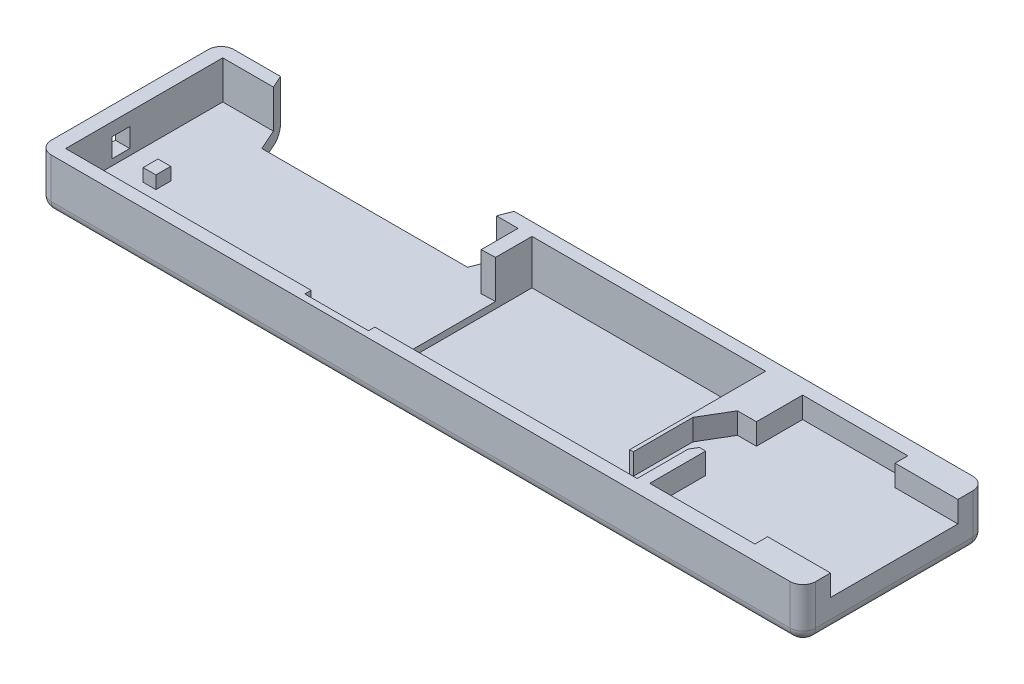
SolidWorks part; units mm, degrees
ref_plane "前视基准面" through (0, 0, 0) normal (0, 0, 1) x (1, 0, 0)
ref_plane "上视基准面" through (0, 0, 0) normal (0, 1, 0) x (1, 0, 0)
ref_plane "右视基准面" through (0, 0, 0) normal (1, 0, 0) x (0, 0, -1)
sketch "草图3" plane through (0, 0, 0) normal (0, 1, 0) x (1, 0, 0)
  line L1 (-39.9314, 29.2531) -> (140.0686, 29.2531)
  line L2 (-39.9314, 29.2531) -> (-39.9314, -13.7469)
  line L3 (-39.9314, -13.7469) -> (140.0686, -13.7469)
  line L4 (140.0686, 29.2531) -> (140.0686, -13.7469)
extrude "凸台-拉伸1" add sketch "草图3" along normal blind 12
sketch "草图4" plane through (0, 0, 0) normal (0, 1, 0) x (1, 0, 0)
  line L0 (-22.4696, -5.8589) -> (26.0023, -5.8589)
  line L1 (-39.9314, -13.7469) -> (140.0686, -13.7469) construction
  line L2 (-25.9314, -13.7469) -> (29.0686, -13.7469)
  line L5 (-25.9314, -13.7469) -> (-22.4696, -5.8589)
  line L6 (29.0686, -13.7469) -> (26.0023, -5.8589)
  point P11 (-22.4696, -5.8589)
  point P12 (26.0023, -5.8589)
extrude "切除-拉伸1" cut sketch "草图4" along normal blind 52
sketch "草图5" plane through (0, 12, 0) normal (0, 1, 0) x (1, 0, 0)
  line L6 (140.0686, -13.7469) -> (140.0686, 29.2531) construction
  line L7 (140.0686, 7.7531) -> (140.0686, 22.7531)
  line L8 (140.0686, 7.7531) -> (140.0686, -7.2469)
  line L9 (140.0686, 22.7531) -> (125.2765, 22.7531)
  line L10 (125.2765, 22.7531) -> (125.2765, -7.2469)
  line L11 (125.2765, -7.2469) -> (140.0686, -7.2469)
  point P0 (140.0686, 7.7531)
extrude "切除-拉伸2" cut sketch "草图5" against normal blind 5
sketch "草图7" plane through (0, 12, 0) normal (0, 1, 0) x (1, 0, 0)
  line L0 (125.2765, 22.7531) -> (125.2765, -7.2469) construction
  line L1 (125.2765, 7.7531) -> (125.2765, 25.7531)
  line L2 (125.2765, 7.7531) -> (125.2765, -10.2469)
  line L3 (125.2765, -10.2469) -> (100.5008, -10.2469)
  line L4 (100.5008, -10.2469) -> (100.5008, 25.7531)
  line L5 (100.5008, 25.7531) -> (125.2765, 25.7531)
  point P0 (125.2765, 7.7531)
extrude "切除-拉伸3" cut sketch "草图7" against normal blind 5
sketch "草图8" plane through (0, 12, 0) normal (0, 1, 0) x (1, 0, 0)
  line L1 (36.2763, 26.2531) -> (91.2763, 26.2531)
  line L2 (36.2763, 26.2531) -> (36.2763, -10.7469)
  line L3 (36.2763, -10.7469) -> (91.2763, -10.7469)
  line L4 (91.2763, 26.2531) -> (91.2763, -10.7469)
  line L6 (140.0686, 29.2531) -> (-39.9314, 29.2531) construction
  line L7 (29.0686, -13.7469) -> (140.0686, -13.7469) construction
  dimension "D1" = 3
  dimension "D2" = 3
extrude "切除-拉伸4" cut sketch "草图8" against normal blind 10.5
sketch "草图9" plane through (0, 12, 0) normal (0, 1, 0) x (1, 0, 0)
  line L0 (91.2763, -10.7469) -> (91.2763, 26.2531) construction
  line L1 (91.2763, 26.2531) -> (98.0396, 26.2531)
  line L2 (91.2763, 26.2531) -> (91.2763, 21.2551)
  line L4 (98.0396, 26.2531) -> (98.0396, 22.1306)
  line L5 (100.5008, 25.7531) -> (100.5008, -10.2469) construction
  line L7 (92.1327, 21.2551) -> (92.1327, 7.2269)
  line L12 (96.0473, 0.6296) -> (100.5008, 0.6296)
  line L13 (100.5008, 12.5794) -> (100.5008, 0.6296)
  line L14 (92.1327, 7.2269) -> (96.0473, 0.6296)
  line L15 (98.0396, 14.2797) -> (99.0486, 12.5794)
  line L17 (99.0486, 12.5794) -> (100.5008, 12.5794)
  line L19 (98.0396, 14.2797) -> (98.0396, 22.1306)
  line L20 (92.1327, 21.2551) -> (91.2763, 21.2551)
extrude "切除-拉伸5" cut sketch "草图9" against normal blind 5
sketch "草图10" plane through (0, 12, 0) normal (0, 1, 0) x (1, 0, 0)
  line L4 (-29.1302, -10.7469) -> (32.9986, -10.7469)
  line L5 (-29.1302, -10.7469) -> (-29.1302, -2.0631)
  line L6 (-29.1302, -2.0631) -> (32.9986, -2.0631)
  line L7 (32.9986, -10.7469) -> (32.9986, -2.0631)
extrude "切除-拉伸6" cut sketch "草图10" against normal blind 8
sketch "草图11" plane through (0, 12, 0) normal (0, 1, 0) x (1, 0, 0)
  line L0 (32.9986, -10.7469) -> (-36.5397, -10.7469)
  line L1 (36.2763, 26.2531) -> (36.2763, -10.7469) construction
  line L5 (-36.5397, 26.2531) -> (-36.5397, -10.7469)
  line L9 (36.2763, 26.2531) -> (36.2763, -2.1672)
  line L10 (-36.5397, 26.2531) -> (36.2763, 26.2531)
  line L11 (32.9986, -10.7469) -> (32.9986, -2.0631)
  line L12 (32.9986, -10.7469) -> (32.9986, -2.0631) construction
  line L13 (32.9986, -2.0631) -> (36.2763, -2.1672)
extrude "切除-拉伸8" cut sketch "草图11" against normal blind 9
fillet "圆角3" radius 3 4 edges at (140.0686, 6, -29.2531) (140.0686, 6, 13.7469) (-39.9314, 6, 13.7469) (-39.9314, 6, -29.2531)
fillet "圆角4" radius 2.5 9 edges at (50.0686, 0, -29.2531) (-39.0527, 0, 12.8682) (-31.4314, 0, 13.7469) (83.0686, 0, 13.7469) (139.1899, 0, 12.8682) (140.0686, 0, -7.7531) (139.1899, 0, -28.3744) (-39.0527, 0, -28.3744) (-39.9314, 0, -7.7531)
sketch "草图12" plane through (0, 12, 0) normal (0, 1, 0) x (1, 0, 0)
  line L1 (36.2763, 26.2531) -> (21.2763, 26.2531)
  line L2 (36.2763, 26.2531) -> (36.2763, 27.7531)
  line L3 (36.2763, 27.7531) -> (21.2763, 27.7531)
  line L4 (21.2763, 26.2531) -> (21.2763, 27.7531)
  dimension "D1" = 15
  dimension "D2" = 1.5
extrude "切除-拉伸9" cut sketch "草图12" against normal blind 5.5
sketch "草图14" plane through (-36.5397, 0, 0) normal (1, 0, 0) x (0, 0, -1)
  line L0 (26.2531, 12) -> (-10.7469, 12) construction
  line L1 (13.2531, 12) -> (13.2531, 8.95)
  line L2 (11.1531, 8.95) -> (15.3531, 8.95)
  line L3 (11.1531, 8.95) -> (11.1531, 4.45)
  line L4 (11.1531, 4.45) -> (15.3531, 4.45)
  line L5 (15.3531, 8.95) -> (15.3531, 4.45)
  line L6 (26.2531, 3) -> (-10.7469, 3) construction
  point P0 (13.2531, 12)
  point P8 (13.2531, 8.95)
  dimension "D1" = 13
  dimension "D2" = 1.45
  dimension "D3" = 4.5
  dimension "D4" = 4.2
extrude "切除-拉伸10" cut sketch "草图14" against normal blind 5.5 contours L5 L2 L3 L4
sketch "草图15" plane through (0, 3, 0) normal (0, 1, 0) x (1, 0, 0)
  line L0 (36.2763, 26.2531) -> (-36.5397, 26.2531) construction
  line L1 (-29.5397, 15.0031) -> (-26.5397, 15.0031)
  line L2 (-29.5397, 15.0031) -> (-29.5397, 11.5031)
  line L3 (-29.5397, 11.5031) -> (-26.5397, 11.5031)
  line L4 (-26.5397, 15.0031) -> (-26.5397, 11.5031)
  line L5 (-36.5397, 26.2531) -> (-36.5397, -10.7469) construction
  point P4 (-29.5397, 13.2531)
  dimension "D1" = 13
  dimension "D2" = 7
  dimension "D3" = 3
  dimension "D4" = 3.5
extrude "凸台-拉伸2" add sketch "草图15" along normal blind 3
ref_plane "基准面1" through (0, 0, -39.2531) normal (0, 0, -1) x (-1, 0, 0)
mirror "镜向3" about plane through (0, 0, -39.2531) normal (0, 0, -1) of bodies 116
delete or keep bodies "实体-删除/保留 1" type delete bodies bodies 116
